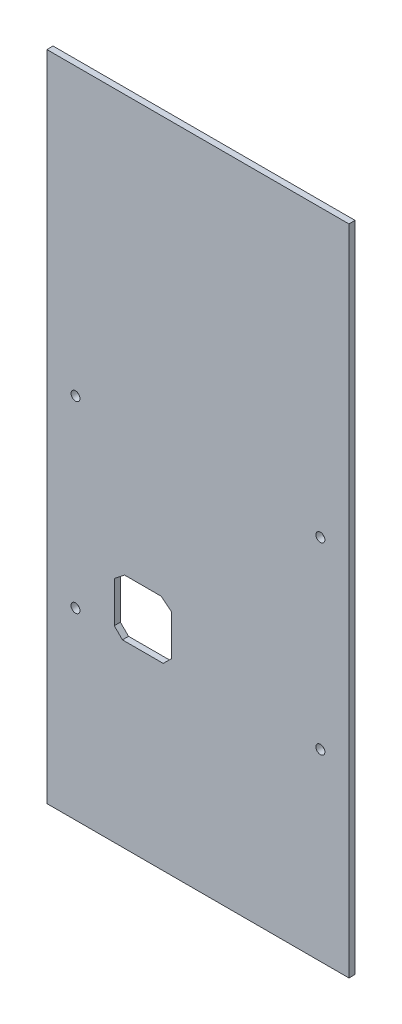
SolidWorks part; units mm, degrees
ref_plane "Plan de face" through (0, 0, 0) normal (0, 0, 1) x (1, 0, 0)
ref_plane "Plan de dessus" through (0, 0, 0) normal (0, 1, 0) x (1, 0, 0)
ref_plane "Plan de droite" through (0, 0, 0) normal (1, 0, 0) x (0, 0, -1)
sketch "Esquisse1" plane through (0, 0, 0) normal (0, 0, 1) x (1, 0, 0)
  line L0 (0, 0) -> (74, 0) construction
  line L1 (0, 0) -> (-74, 0) construction
  line L2 (-74, 0) -> (-74, 165) construction
  line L3 (-74, 165) -> (74, 165)
  line L4 (74, 165) -> (74, -165)
  line L5 (74, -165) -> (-74, -165)
  line L7 (-74, 165) -> (-74, -165)
  dimension "D1" = 165
  dimension "D2" = 74
  dimension "D4" = 330
  dimension "D5" = 330
extrude "Boss.-Extru.1" add sketch "Esquisse1" along normal blind 3
sketch "Esquisse3" plane through (0, 0, 3) normal (0, 0, 1) x (1, 0, 0)
  line L0 (-60, -165) -> (60, -165) construction
  line L1 (-74, -165) -> (74, -165) construction
  line L2 (60, -165) -> (60, -75) construction
  line L3 (0, -1.65) -> (0, 1.65) construction
  line L6 (-60, -165) -> (0, -165) construction
  line L7 (60, -75) -> (60, 15) construction
  circle A0 centre (60, -75) radius 2.2
  circle A3 centre (60, 15) radius 2.2
  point P10 (0, -165)
  dimension "D3" = 60
  dimension "D4" = 90
  dimension "D1" = 60
  dimension "D2" = 90
extrude "Enlèv. mat.-Extru.2" cut sketch "Esquisse3" against normal up to next
sketch "Esquisse4" plane through (0, 0, 3) normal (0, 0, 1) x (1, 0, 0)
  line L0 (-74, 165) -> (-74, 155)
  line L1 (-74, 165) -> (-74, -165) construction
  line L2 (-74, 155) -> (74, 155)
  line L3 (74, -165) -> (74, 165) construction
  line L4 (74, 155) -> (74, 165)
  line L5 (74, 165) -> (-74, 165)
extrude "Enlèv. mat.-Extru.3" cut sketch "Esquisse4" against normal up to next
mirror "Symétrie1" about plane through (0, 0, 0) normal (1, 0, 0) of "Enlèv. mat.-Extru.2"
sketch "Esquisse5" plane through (0, 0, 0) normal (0, 0, -1) x (-1, 0, 0)
  line L0 (74, -165) -> (60, -165) construction
  line L1 (74, -165) -> (-74, -165) construction
  line L2 (60, -165) -> (60, -63) construction
  line L3 (60, -63) -> (41, -63) construction
  line L4 (27, -63) -> (27, -49) construction
  line L5 (17, -77) -> (37, -77)
  line L6 (37, -77) -> (41, -77) construction
  line L7 (41, -77) -> (41, -73) construction
  line L8 (41, -73) -> (37, -77)
  line L11 (41, -53) -> (41, -49) construction
  line L12 (41, -49) -> (36, -49) construction
  line L15 (13, -63) -> (41, -63) construction
  line L16 (27, -77) -> (27, -63) construction
  line L17 (36, -49) -> (41, -53)
  line L18 (18, -49) -> (36, -49)
  line L23 (41, -63) -> (41, -73)
  line L24 (41, -53) -> (41, -63)
  line L25 (13, -49) -> (18, -49) construction
  line L26 (13, -53) -> (13, -49) construction
  line L27 (13, -77) -> (13, -73) construction
  line L28 (17, -77) -> (13, -77) construction
  line L29 (27, -63) -> (27, -165) construction
  line L30 (13, -53) -> (13, -63)
  line L31 (13, -63) -> (13, -73)
  line L32 (18, -49) -> (13, -53)
  line L33 (13, -73) -> (17, -77)
  point P17 (41, -63)
  dimension "D1" = 102
  dimension "D2" = 10
  dimension "D3" = 14
  dimension "D4" = 14
  dimension "D7" = 5.6569
  dimension "D9" = 4
  dimension "D11" = 33
extrude "Enlèv. mat.-Extru.4" cut sketch "Esquisse5" against normal up to next
